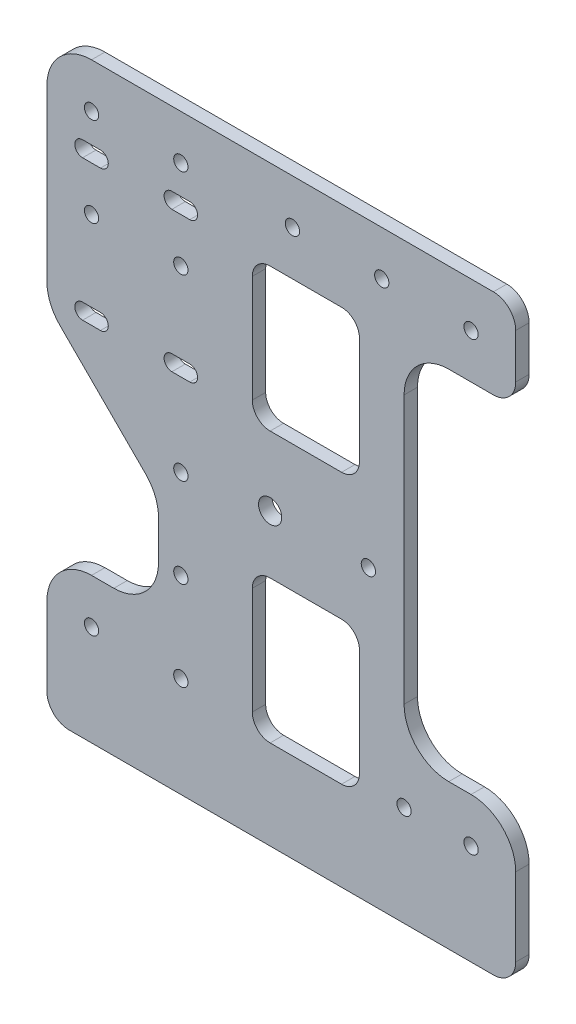
SolidWorks part; units mm, degrees
material "Thornel Mat VMA"
ref_plane "前视基准面" through (0, 0, 0) normal (0, 0, 1) x (1, 0, 0)
ref_plane "上视基准面" through (0, 0, 0) normal (0, 1, 0) x (1, 0, 0)
ref_plane "右视基准面" through (0, 0, 0) normal (1, 0, 0) x (0, 0, -1)
sketch "草图1" plane through (0, 0, 0) normal (0, 0, 1) x (1, 0, 0)
  line L0 (60, 77.5) -> (-30, 77.5)
  line L1 (0, 77.5) -> (100, 77.5) construction
  line L2 (0, 77.5) -> (0, 57.5) construction
  line L3 (0, 57.5) -> (100, 57.5) construction
  line L4 (100, 77.5) -> (100, 57.5) construction
  line L5 (20, 20) -> (100, 20) construction
  line L6 (20, 20) -> (20, 0) construction
  line L7 (20, 0) -> (100, 0) construction
  line L8 (100, 20) -> (100, 0) construction
  line L9 (20, 20) -> (0, 20) construction
  line L10 (20, 20) -> (20, 0) construction
  line L11 (20, 0) -> (0, 0) construction
  line L12 (0, 20) -> (0, 0) construction
  line L13 (-40, 57.5) -> (0, 57.5) construction
  line L14 (-40, 57.5) -> (-40, 29.5) construction
  line L15 (-40, 29.5) -> (0, 29.5) construction
  line L16 (0, 57.5) -> (0, 29.5) construction
  line L17 (-40, 67.5) -> (-40, 29.5)
  line L18 (-37.0711, 22.4289) -> (-17.9289, 3.2868)
  line L19 (-15, -3.7843) -> (-15, -12.5)
  line L20 (-25, -22.5) -> (-30, -22.5)
  line L21 (-40, -32.5) -> (-40, -50)
  line L24 (-30, 67.5) -> (-10, 67.5) construction
  line L25 (-30, 67.5) -> (-30, -32.5) construction
  line L26 (40, -12.5) -> (40, 47.5)
  line L27 (50, 57.5) -> (60, 57.5)
  line L28 (65, 62.5) -> (65, 72.5)
  line L29 (-35, -55) -> (60, -55)
  line L30 (65, -50) -> (65, -32.5)
  line L31 (55, -22.5) -> (50, -22.5)
  line L32 (-32, 27.75) -> (-28, 27.75) construction
  line L33 (-32, 29.5) -> (-28, 29.5)
  line L34 (-32, 26) -> (-28, 26)
  line L35 (-12, 27.75) -> (-8, 27.75) construction
  line L36 (-12, 29.5) -> (-8, 29.5)
  line L37 (-12, 26) -> (-8, 26)
  line L38 (-12, 59.25) -> (-8, 59.25) construction
  line L39 (-12, 61) -> (-8, 61)
  line L40 (-12, 57.5) -> (-8, 57.5)
  line L41 (-32, 59.25) -> (-28, 59.25) construction
  line L42 (-32, 61) -> (-28, 61)
  line L43 (-32, 57.5) -> (-28, 57.5)
  line L44 (-32, 27.75) -> (-12, 27.75) construction
  line L45 (-32, 27.75) -> (-32, 59.25) construction
  line L46 (6, -7) -> (6, -31)
  line L47 (10, 57.5) -> (26, 57.5)
  line L48 (6, 53.5) -> (6, 29.5)
  line L49 (10, 25.5) -> (26, 25.5)
  line L50 (30, 53.5) -> (30, 29.5)
  line L51 (10, -3) -> (26, -3)
  line L52 (30, -7) -> (30, -31)
  line L53 (10, -35) -> (26, -35)
  arc A0 (-40, 29.5) -> (-37.0711, 22.4289) centre (-30, 29.5) ccw
  arc A1 (-17.9289, 3.2868) -> (-15, -3.7843) centre (-25, -3.7843) cw
  circle A2 centre (-30, 67.5) radius 1.6
  circle A3 centre (-10, 67.5) radius 1.6
  circle A4 centre (-10, -32.5) radius 1.6
  circle A5 centre (-30, -32.5) radius 1.6
  arc A6 (-30, 77.5) -> (-40, 67.5) centre (-30, 67.5) ccw
  arc A7 (-15, -12.5) -> (-25, -22.5) centre (-25, -12.5) cw
  arc A8 (-30, -22.5) -> (-40, -32.5) centre (-30, -32.5) ccw
  circle A9 centre (10, 10) radius 2.6
  arc A10 (40, 47.5) -> (50, 57.5) centre (50, 47.5) cw
  arc A11 (65, -32.5) -> (55, -22.5) centre (55, -32.5) ccw
  arc A12 (50, -22.5) -> (40, -12.5) centre (50, -12.5) cw
  arc A13 (60, 77.5) -> (65, 72.5) centre (60, 72.5) cw
  arc A14 (60, 57.5) -> (65, 62.5) centre (60, 62.5) ccw
  arc A15 (60, -55) -> (65, -50) centre (60, -50) ccw
  arc A16 (-35, -55) -> (-40, -50) centre (-35, -50) cw
  circle A17 centre (15, 67.5) radius 1.6
  circle A18 centre (55, 67.5) radius 1.6
  circle A19 centre (32, 10) radius 1.6
  circle A20 centre (35, 67.5) radius 1.6
  arc A21 (-32, 29.5) -> (-32, 26) centre (-32, 27.75) ccw
  arc A22 (-28, 26) -> (-28, 29.5) centre (-28, 27.75) ccw
  arc A23 (-12, 29.5) -> (-12, 26) centre (-12, 27.75) ccw
  arc A24 (-8, 26) -> (-8, 29.5) centre (-8, 27.75) ccw
  arc A25 (-12, 61) -> (-12, 57.5) centre (-12, 59.25) ccw
  arc A26 (-8, 57.5) -> (-8, 61) centre (-8, 59.25) ccw
  arc A27 (-32, 61) -> (-32, 57.5) centre (-32, 59.25) ccw
  arc A28 (-28, 57.5) -> (-28, 61) centre (-28, 59.25) ccw
  arc A29 (26, 57.5) -> (30, 53.5) centre (26, 53.5) cw
  arc A30 (6, 29.5) -> (10, 25.5) centre (10, 29.5) ccw
  arc A31 (26, 25.5) -> (30, 29.5) centre (26, 29.5) ccw
  arc A32 (10, 57.5) -> (6, 53.5) centre (10, 53.5) ccw
  arc A33 (10, -3) -> (6, -7) centre (10, -7) ccw
  arc A34 (6, -31) -> (10, -35) centre (10, -31) ccw
  arc A35 (26, -3) -> (30, -7) centre (26, -7) cw
  arc A36 (26, -35) -> (30, -31) centre (26, -31) ccw
  circle A37 centre (40, -32.5) radius 1.6
  circle A38 centre (55, -32.5) radius 1.6
  circle A39 centre (-10, -12.5) radius 1.6
  circle A40 centre (-10, 7.5) radius 1.6
  circle A41 centre (-10, 47.5) radius 1.6
  circle A42 centre (-30, 47.5) radius 1.6
  point P42 (10, 20)
  point P44 (20, 10)
  point P54 (40, 57.5)
  point P61 (65, 77.5)
  point P64 (65, 57.5)
  point P78 (65, 67.5)
  point P79 (-30, 27.75)
  point P89 (-10, 27.75)
  point P96 (-10, 59.25)
  point P103 (-30, 59.25)
  point P142 (0, 0)
  dimension "D14" = 10
  dimension "D15" = 3.2
  dimension "D16" = 10
  dimension "D19" = 10
  dimension "D20" = 5.2
  dimension "D21" = 10
  dimension "D22" = 10
  dimension "D23" = 5
  dimension "D25" = 5
  dimension "D40" = 4
  dimension "D46" = 20
  dimension "D49" = 3.2
  dimension "D1" = 20
  dimension "D2" = 20
  dimension "D3" = 20
  dimension "D4" = 77.5
  dimension "D5" = 40
  dimension "D6" = 28
  dimension "D7" = 100
  dimension "D8" = 80
  dimension "D11" = 90
  dimension "D12" = 20
  dimension "D13" = 100
  dimension "D17" = 25
  dimension "D18" = 45
  dimension "D24" = 20
  dimension "D26" = 55
  dimension "D27" = 8
  dimension "D28" = 10
  dimension "D29" = 20
  dimension "D30" = 20
  dimension "D33" = 90
  dimension "D34" = 3.5
  dimension "D35" = 1.75
  dimension "D36" = 1.75
  dimension "D37" = 4
  dimension "D38" = 10
  dimension "D39" = 20
  dimension "D42" = 10
  dimension "32" = 32
  dimension "D43" = 24
  dimension "D44" = 20
  dimension "D45" = 20
  dimension "D47" = 20
  dimension "D48" = 15
  dimension "D9" = 2
  dimension "D10" = 2
  dimension "D31" = 2
  dimension "D32" = 2
  dimension "D41" = 2
extrude "凸台-拉伸1" add sketch "草图1" along normal mid plane 3
